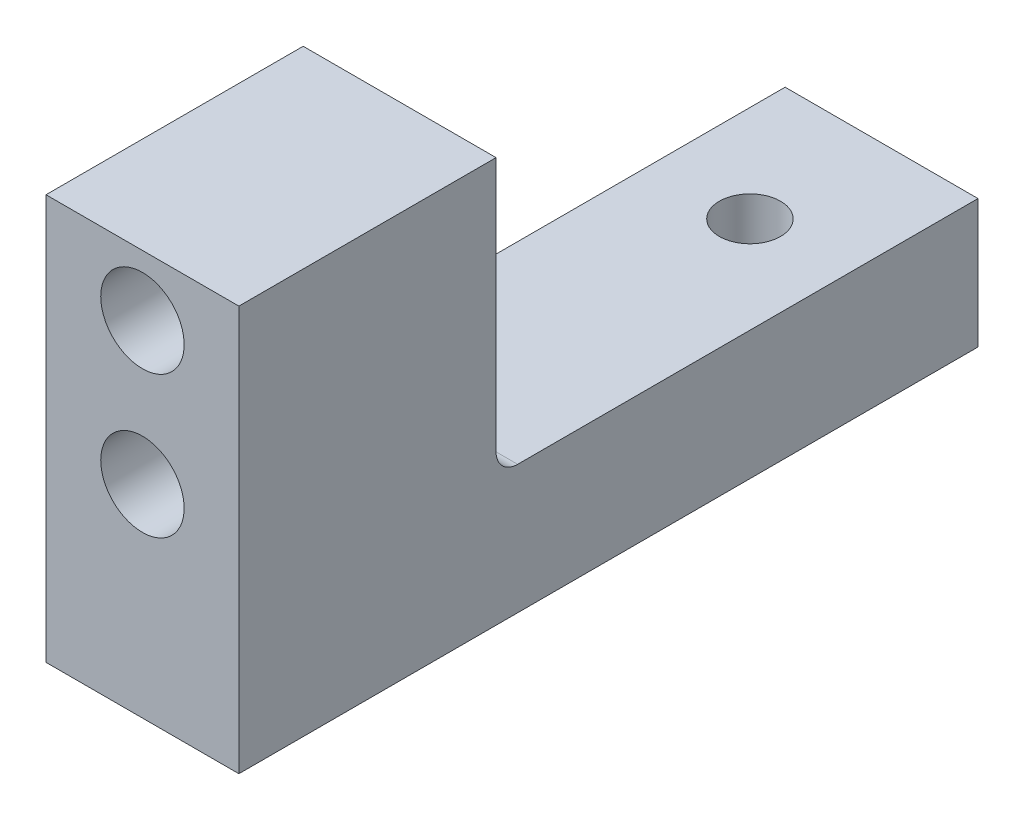
SolidWorks part; units mm, degrees
ref_plane "Front Plane" through (0, 0, 0) normal (0, 0, 1) x (1, 0, 0)
ref_plane "Top Plane" through (0, 0, 0) normal (0, 1, 0) x (1, 0, 0)
ref_plane "Right Plane" through (0, 0, 0) normal (1, 0, 0) x (0, 0, -1)
sketch "Sketch1" plane through (0, 0, 0) normal (1, 0, 0) x (0, 0, -1)
  line L1 (-9.125, 5) -> (9.125, 5)
  line L2 (-9.125, 5) -> (-9.125, -5)
  line L3 (-9.125, -5) -> (9.125, -5)
  line L4 (9.125, 5) -> (9.125, -5)
  line L5 (-9.125, 5) -> (9.125, -5) construction
  line L6 (-9.125, -5) -> (9.125, 5) construction
  point P0 (0, 0)
  dimension "D1" = 10
  dimension "D2" = 18.25
extrude "Boss-Extrude1" add sketch "Sketch1" along normal blind 4.7625
hole_wizard "#1-64 Tapped Hole1" positions "Sketch4" profile "Sketch3" tap size "#1-64" standard "ANSI Inch"
sketch "Sketch4" plane through (0, -5, 0) normal (0, -1, 0) x (-1, 0, 0)
  line L0 (-2.3813, -9.125) -> (-2.3813, 9.125) construction
  line L1 (-4.7625, -9.125) -> (0, -9.125) construction
  line L2 (-4.7625, 9.125) -> (0, 9.125) construction
  point P0 (-2.3813, -6.125)
  point P2 (-2.3812, 5.875)
  dimension "D1" = 3
  dimension "D2" = 15
cosmetic thread "Hole Thread1" parameters "D1"=3.175, "D2"=1.8542
cosmetic thread "Hole Thread2" parameters "D1"=3.5, "D2"=1.8542
sketch "Sketch3" plane through (2.3813, -5, 6.125) normal (1, 0, 0) x (0, 0, -1)
  line L0 (0, 0) -> (0, 3.954)
  line L1 (0, 3.954) -> (0.7556, 3.5)
  line L2 (0.7556, 3.5) -> (0.7556, 0)
  line L5 (0.7556, 0) -> (0, 0)
  line L10 (0, 3.954) -> (-0.7557, 3.5) construction
  line L11 (0, -6.35) -> (0, 107.95) construction
  dimension "Tap Drill Dia." = 1.5113
  dimension "Tap Drill Depth" = 3.5
  dimension "Drill Angle" = 118
sketch "Sketch5" plane through (4.7625, 0, 0) normal (1, 0, 0) x (0, 0, -1)
  line L0 (-9.125, -5) -> (9.125, -5) construction
  line L1 (9.125, 5) -> (-2.775, 5)
  line L2 (9.125, 5) -> (9.125, -1.825)
  line L3 (9.125, -1.825) -> (-2.775, -1.825)
  line L4 (-2.775, 5) -> (-2.775, -1.825)
  line L5 (-9.125, 5) -> (-9.125, -5) construction
  dimension "D1" = 3.175
  dimension "D2" = 6.35
extrude "Cut-Extrude2" cut sketch "Sketch5" against normal blind 10
fillet "Fillet1" radius 0.5334 1 edges at (2.3813, -1.825, 2.775)
sketch "Sketch2" plane through (0, 0, -9.125) normal (0, 0, -1) x (-1, 0, 0)
  line L0 (-2.3813, 5) -> (-2.3813, -5) construction
  line L1 (-4.7625, 5) -> (0, 5) construction
  line L2 (-4.7625, -5) -> (0, -5) construction
  circle A0 centre (-2.3813, 3.5) radius 1.03
  circle A1 centre (-2.3813, 0) radius 1.03
  dimension "D1" = 2.06
  dimension "D2" = 2.06
  dimension "D3" = 1.5
  dimension "D4" = 5
extrude "Cut-Extrude1" cut sketch "Sketch2" against normal through all
sketch "Sketch6" plane through (0, 0, 2.775) normal (0, 0, -1) x (-1, 0, 0)
  circle A0 centre (-2.3813, 0) radius 1.2192 construction
  circle A1 centre (-2.3813, 3.5) radius 1.2192 construction
  dimension "D1" = 2.4384
  dimension "D2" = 2.4384
equation "\"D2@Sketch6\"=\"D1@Sketch6\""
